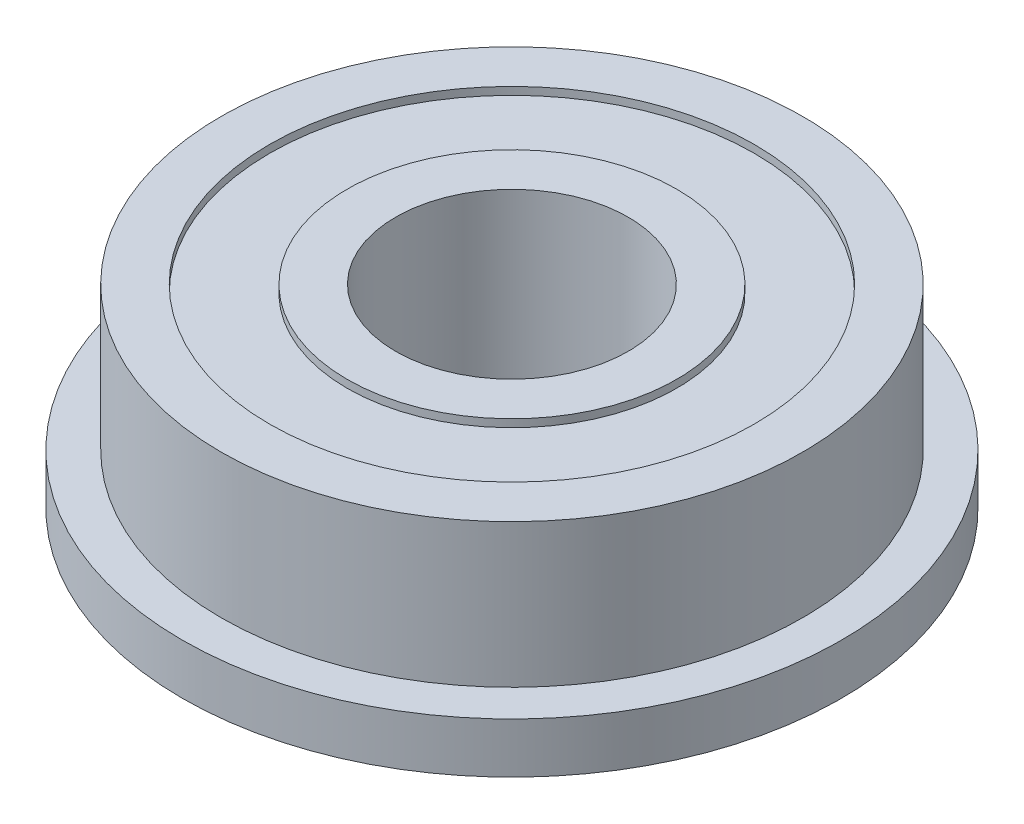
SolidWorks part; units mm, degrees
ref_plane "前视基准面" through (0, 0, 0) normal (0, 0, 1) x (1, 0, 0)
ref_plane "上视基准面" through (0, 0, 0) normal (0, 1, 0) x (1, 0, 0)
ref_plane "右视基准面" through (0, 0, 0) normal (1, 0, 0) x (0, 0, -1)
sketch "草图1" plane through (0, 0, 0) normal (0, 1, 0) x (1, 0, 0)
  circle A0 centre (0, 0) radius 8.5
  dimension "D1" = 17
extrude "凸台-拉伸1" add sketch "草图1" along normal blind 1.3
sketch "草图2" plane through (0, 1.3, 0) normal (0, 1, 0) x (1, 0, 0)
  circle A0 centre (0, 0) radius 7.5
  dimension "D1" = 15
extrude "凸台-拉伸2" add sketch "草图2" along normal offset from surface (3.7 mm away) 5 up to face at (0, 0, 8.5)
sketch "草图3" plane through (0, 5, 0) normal (0, 1, 0) x (1, 0, 0)
  circle A0 centre (0, 0) radius 3
  dimension "D1" = 6
extrude "切除-拉伸1" cut sketch "草图3" against normal up to next
sketch "草图4" plane through (0, 5, 0) normal (0, 1, 0) x (1, 0, 0)
  circle A0 centre (0, 0) radius 4.25
  circle A1 centre (0, 0) radius 6.25
  dimension "D1" = 8.5
  dimension "D2" = 12.5
extrude "切除-拉伸2" cut sketch "草图4" against normal blind 0.2
sketch "草图5" plane through (0, 0, 0) normal (0, -1, 0) x (1, 0, 0)
  circle A0 centre (0, 0) radius 4.25
  circle A1 centre (0, 0) radius 6.25
  dimension "D1" = 8.5
  dimension "D2" = 12.5
extrude "切除-拉伸3" cut sketch "草图5" against normal blind 0.2
